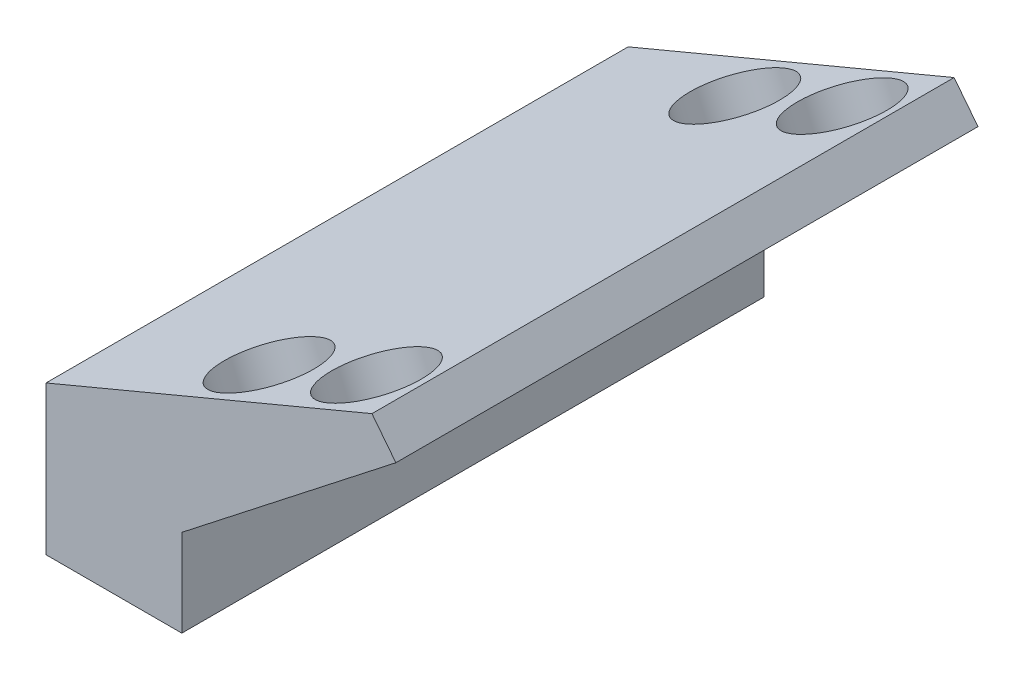
SolidWorks part; units mm, degrees
ref_plane "前视基准面" through (0, 0, 0) normal (0, 0, 1) x (1, 0, 0)
ref_plane "上视基准面" through (0, 0, 0) normal (0, 1, 0) x (1, 0, 0)
ref_plane "右视基准面" through (0, 0, 0) normal (1, 0, 0) x (0, 0, -1)
other "Configuration Table"
sketch "草图1" plane through (0, 0, 0) normal (0, 0, 1) x (1, 0, 0)
  line L0 (0, 0) -> (7, 0)
  line L1 (7, 0) -> (7, 4.5)
  line L2 (7, 4.5) -> (18.0303, 13.1216)
  line L3 (18.0303, 13.1216) -> (16.7987, 14.6973)
  line L4 (16.7987, 14.6973) -> (0, 7.6683)
  line L5 (0, 7.6683) -> (0, 0)
  dimension "D1" = 7
  dimension "D2" = 4.5
  dimension "D3" = 14
  dimension "D4" = 2
  dimension "D5" = 7.6683
  dimension "D6" = 16.7987
extrude "凸台-拉伸1" add sketch "草图1" along normal blind 30 contours L2 L3 L4 L5 L0 L1
ref_plane "基准面1" through (16.7987, 14.6973, 30) normal (0, 0, -1) x (-1, 0, 0)
sketch "草图3" plane through (-2.7306, 6.5257, 0) normal (-0.386, 0.9225, 0) x (0.9225, 0.386, 0)
  line L0 (21.1699, 0) -> (2.96, 0) construction
  line L1 (29.4199, -30) -> (12.9199, -30) construction
  line L2 (21.1699, -30) -> (2.96, -30) construction
  line L3 (21.1699, -30) -> (21.1699, 0) construction
  circle A0 centre (18.1699, -3) radius 2.5
  circle A1 centre (12.1699, -3) radius 2.5
  circle A2 centre (18.1699, -27) radius 2.5
  circle A3 centre (12.1699, -27) radius 2.5
  point P8 (11.4496, -2.9232)
  point P9 (11.4496, -25.9186)
  dimension "D1" = 5
  dimension "D2" = 5
  dimension "D3" = 5
  dimension "D4" = 5
  dimension "D9" = 3
  dimension "D5" = 3
  dimension "D6" = 3
  dimension "D7" = 3
  dimension "D8" = 3
  dimension "D10" = 9
  dimension "D11" = 3
  dimension "D12" = 9
extrude "切除-拉伸1" cut sketch "草图3" against normal blind 25
sketch "草图4" plane through (0, 0, 30) normal (0, 0, 1) x (1, 0, 0)
  line L0 (0, 7.6683) -> (-6.6511, 4.8852)
  line L1 (-6.6511, 4.8852) -> (-6.6511, 0)
  line L2 (-6.6511, 0) -> (0, 0)
  line L3 (0, 0) -> (0, 7.6683)
  line L4 (16.7987, 14.6973) -> (0, 7.6683) construction
  dimension "D1" = 180
  dimension "D2" = 4.8852
